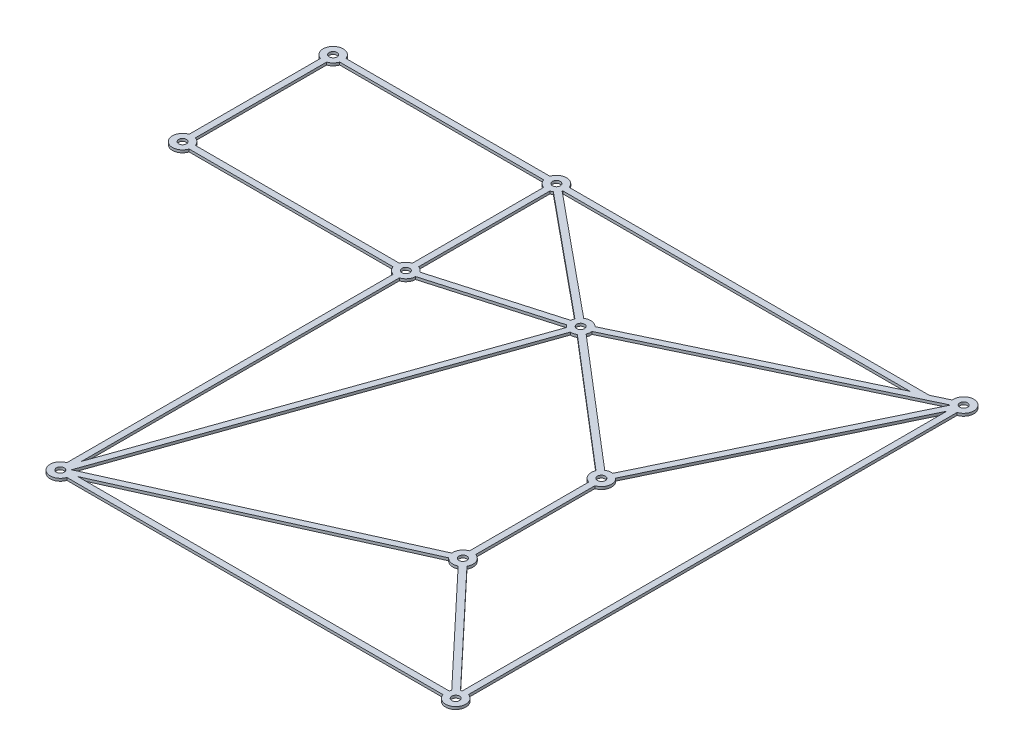
SolidWorks part; units mm, degrees
ref_plane "Front Plane" through (0, 0, 0) normal (0, 0, 1) x (1, 0, 0)
ref_plane "Top Plane" through (0, 0, 0) normal (0, 1, 0) x (1, 0, 0)
ref_plane "Right Plane" through (0, 0, 0) normal (1, 0, 0) x (0, 0, -1)
sketch "Sketch1" plane through (0, 0, 0) normal (0, 1, 0) x (1, 0, 0)
  line L0 (106.9742, -89.6492) -> (106.9742, -142.975) construction
  line L7 (0, -191.1) -> (152.3, -191.1) construction
  line L8 (152.3, -191.1) -> (152.3, 4.565) construction
  line L9 (106.9742, -89.6492) -> (106.9742, -142.975) construction
  line L10 (0, -191.1) -> (106.9742, -142.975) construction
  line L11 (106.9742, -142.975) -> (152.3, -191.1) construction
  line L12 (52.3, -42.975) -> (106.9742, -89.6492) construction
  line L13 (106.9742, -89.6492) -> (152.3, 4.565) construction
  line L14 (152.3, 4.565) -> (52.3, -42.975) construction
  line L15 (52.3, -42.975) -> (0, -191.1) construction
  line L16 (0, -192.3) -> (152.3, -192.3)
  line L17 (0.4923, -192.1944) -> (107.4665, -144.0694)
  line L18 (106.1006, -143.7977) -> (151.4264, -191.9227)
  line L19 (105.7742, -89.6492) -> (105.7742, -142.975)
  line L20 (153.5, -191.1) -> (153.5, 4.565)
  line L21 (108.0556, -90.1694) -> (153.3814, 4.0448)
  line L22 (151.7848, 5.6488) -> (51.7848, -41.8912)
  line L23 (51.5209, -43.8877) -> (106.1951, -90.5619)
  line L24 (51.1685, -42.5755) -> (-1.1315, -190.7005)
  line L25 (0, -189.9) -> (152.3, -189.9)
  line L26 (-0.4923, -190.0056) -> (106.4819, -141.8806)
  line L27 (107.8478, -142.1523) -> (153.1736, -190.2773)
  line L28 (108.1742, -89.6492) -> (108.1742, -142.975)
  line L29 (151.1, -191.1) -> (151.1, 4.565)
  line L30 (105.8928, -89.129) -> (151.2186, 5.0852)
  line L31 (152.8152, 3.4812) -> (52.8152, -44.0588)
  line L32 (53.0791, -42.0623) -> (107.7533, -88.7365)
  line L33 (53.4315, -43.3745) -> (1.1315, -191.4995)
  circle A1 centre (0, 0) radius 3.9 construction
  circle A2 centre (52.3, -42.975) radius 1.5
  circle A3 centre (152.3, 4.565) radius 1.5
  circle A4 centre (152.3, -191.1) radius 1.5
  circle A5 centre (0, -191.1) radius 1.5
  circle A6 centre (106.9742, -89.6492) radius 1.5
  circle A7 centre (106.9742, -142.975) radius 1.5
  circle A8 centre (106.9742, -89.6492) radius 3.9
  circle A9 centre (106.9742, -142.975) radius 3.9
  circle A10 centre (152.3, -191.1) radius 3.9
  circle A11 centre (0, -191.1) radius 3.9
  circle A12 centre (52.3, -42.975) radius 3.9
  circle A13 centre (152.3, 4.565) radius 3.9
  dimension "D11" = 3
  dimension "D2" = 4.565
  dimension "D3" = 195.665
  dimension "D4" = 152.3
  dimension "D5" = 52.3
  dimension "D6" = 42.975
  dimension "D7" = 53.3258
  dimension "D8" = 46.6742
  dimension "D9" = 54.6742
  dimension "D10" = 152.3
  dimension "D12" = 2.4
  dimension "D13" = 1.2
  dimension "D14" = 1.2
extrude "Boss-Extrude1" add sketch "Sketch1" along normal blind 20
sketch "Sketch2" plane through (0, 20, 0) normal (0, 1, 0) x (1, 0, 0)
  line L0 (153.5, -187.3892) -> (153.5, 0.8542) construction
  line L1 (151.1, -187.3892) -> (151.1, -0.6973) construction
  line L2 (105.7742, -93.36) -> (105.7742, -139.2642) construction
  line L3 (108.1742, -93.36) -> (108.1742, -139.2642) construction
  line L4 (153.5, -187.3892) -> (153.5, 0.8542)
  line L5 (151.1, -187.3892) -> (151.1, 0.8542)
  line L6 (105.7742, -93.36) -> (105.7742, -139.2642)
  line L7 (108.1742, -93.36) -> (108.1742, -139.2642)
  arc A0 (153.5, 0.8542) -> (148.4334, 4.0555) centre (152.3, 4.565) ccw construction
  arc A1 (55.1361, -40.298) -> (49.933, -46.0746) centre (52.3, -42.975) ccw construction
  arc A2 (108.1742, -93.36) -> (109.6643, -86.8255) centre (106.9742, -89.6492) ccw construction
  arc A3 (110.3919, -144.8536) -> (108.1742, -139.2642) centre (106.9742, -142.975) ccw construction
  arc A4 (148.5892, -192.3) -> (153.5, -187.3892) centre (152.3, -191.1) ccw construction
  arc A5 (0.1039, -187.2014) -> (3.7108, -192.3) centre (0, -191.1) ccw construction
  arc A6 (153.5, 0.8542) -> (148.4334, 4.0555) centre (152.3, 4.565) ccw
  arc A7 (55.1361, -40.298) -> (49.933, -46.0746) centre (52.3, -42.975) ccw
  arc A8 (108.1742, -93.36) -> (109.6643, -86.8255) centre (106.9742, -89.6492) ccw
  arc A9 (110.3919, -144.8536) -> (108.1742, -139.2642) centre (106.9742, -142.975) ccw
  arc A10 (148.5892, -192.3) -> (153.5, -187.3892) centre (152.3, -191.1) ccw
  arc A11 (0.1039, -187.2014) -> (3.7108, -192.3) centre (0, -191.1) ccw
  circle A12 centre (52.3, -42.975) radius 3.9
  circle A13 centre (152.3, 4.565) radius 3.9
  circle A14 centre (106.9742, -89.6492) radius 3.9
  circle A15 centre (0, -191.1) radius 3.9
  circle A16 centre (106.9742, -142.975) radius 3.9
  circle A17 centre (152.3, -191.1) radius 3.9
  circle M1 centre (106.9742, -142.975) radius 1.5
  circle M2 centre (152.3, -191.1) radius 1.5
  arc M5 (104.0824, -145.5918) -> (108.6448, -146.4991) centre (106.9742, -142.975) ccw
  arc M7 (148.8823, -189.2214) -> (148.5892, -189.9) centre (152.3, -191.1) ccw
  circle M8 centre (106.9742, -89.6492) radius 1.5
  line M10 (151.1, -0.6973) -> (151.1, -187.3892)
  arc M11 (151.1, -187.3892) -> (150.6294, -187.5759) centre (152.3, -191.1) ccw
  arc M13 (110.3919, -144.8536) -> (108.1742, -139.2642) centre (106.9742, -142.975) ccw
  line M14 (108.1742, -139.2642) -> (108.1742, -93.36)
  arc M15 (108.1742, -93.36) -> (109.6643, -86.8255) centre (106.9742, -89.6492) ccw
  circle M16 centre (152.3, 4.565) radius 1.5
  arc M17 (55.9014, -44.4716) -> (56.1666, -42.4655) centre (52.3, -42.975) ccw
  arc M19 (149.4639, 1.888) -> (149.6099, 1.7413) centre (152.3, 4.565) ccw
  arc M21 (107.5016, -85.785) -> (104.9311, -86.3272) centre (106.9742, -89.6492) ccw
  line M23 (2.0652, -188.8551) -> (52.1961, -46.8736)
  arc M24 (52.1961, -46.8736) -> (54.3431, -46.297) centre (52.3, -42.975) ccw
  arc M26 (103.3728, -88.1526) -> (105.7742, -93.36) centre (106.9742, -89.6492) ccw
  line M27 (105.7742, -93.36) -> (105.7742, -139.2642)
  arc M28 (105.7742, -139.2642) -> (103.0978, -143.4031) centre (106.9742, -142.975) ccw
  line M29 (103.0978, -143.4031) -> (2.0652, -188.8551)
  arc M31 (55.1361, -40.298) -> (49.933, -46.0746) centre (52.3, -42.975) ccw
  arc M33 (0.1039, -187.2014) -> (3.7108, -192.3) centre (0, -191.1) ccw
  arc M35 (148.5892, -192.3) -> (153.5, -187.3892) centre (152.3, -191.1) ccw
  line M36 (153.5, -187.3892) -> (153.5, 0.8542)
  arc M37 (153.5, 0.8542) -> (148.4334, 4.0555) centre (152.3, 4.565) ccw
  circle M38 centre (52.3, -42.975) radius 1.5
  circle M39 centre (0, -191.1) radius 1.5
extrude "Boss-Extrude2" add sketch "Sketch2" along normal blind 4.8 contours A17 A13 L5 M36 M10 | A13 M37 M19 M16 | A17 M35 M11 M7 M2 | A16 A14 M14 M27 | A16 M5 M13 M28 M1 | A14 M15 M21 M26 M8 | A15 M33 M29 M23 M39 | A12 M24 M17 M31 M38
sketch "Sketch3" plane through (0, 0, 0) normal (0, -1, 0) x (1, 0, 0)
  line L0 (0, 58) -> (0, 0) construction
  line L1 (0, 191.1) -> (0, 58) construction
  line L2 (0, 58) -> (52.3, 42.975) construction
  line L3 (52.3, 42.975) -> (0, 0) construction
  line L4 (0, 0) -> (152.3, 0) construction
  line L5 (-1.2, 191.1) -> (-1.2, 58)
  line L6 (-1.2, 58) -> (-1.2, 0)
  line L7 (-0.3313, 56.8467) -> (49.7736, 42.4522)
  line L8 (49.7736, 42.4522) -> (-0.7618, 0.9271)
  line L9 (0, -1.2) -> (152.3, -1.2)
  line L10 (1.2, 191.1) -> (1.2, 58)
  line L11 (1.2, 58) -> (1.2, 0)
  line L12 (0.3313, 59.1533) -> (54.8264, 43.4978)
  line L13 (54.8264, 43.4978) -> (0.7618, -0.9271)
  line L14 (0, 1.2) -> (152.3, 1.2)
  line L15 (-86, 0) -> (0, 0) construction
  line L16 (-86, 0) -> (-86, 58) construction
  line L17 (-86, 58) -> (0, 58) construction
  line L18 (-84.8, 1.2) -> (0, 1.2)
  line L19 (-84.8, 1.2) -> (-84.8, 56.8)
  line L20 (-84.8, 56.8) -> (0, 56.8)
  line L21 (-87.2, -1.2) -> (0, -1.2)
  line L22 (-87.2, -1.2) -> (-87.2, 59.2)
  line L23 (-87.2, 59.2) -> (0, 59.2)
  circle A0 centre (0, 0) radius 1.5
  circle A1 centre (0, 58) radius 1.5
  circle A2 centre (0, 58) radius 3.9
  circle A3 centre (0, 0) radius 3.9
  circle A4 centre (0, 191.1) radius 1.5 construction
  circle A6 centre (52.3, 42.975) radius 1.5 construction
  circle A7 centre (0, 191.1) radius 1.5
  circle A9 centre (52.3, 42.975) radius 1.5
  arc A11 (54.3431, 46.297) -> (52.1961, 46.8736) centre (52.3, 42.975) ccw construction
  circle A12 centre (-86, 58) radius 3.9
  circle A13 centre (-86, 0) radius 3.9
  circle A14 centre (-86, 58) radius 1.5
  circle A15 centre (-86, 0) radius 1.5
  line M11 (55.1361, 40.298) -> (148.4334, -4.0555)
  arc M12 (148.4334, -4.0555) -> (153.5, -0.8542) centre (152.3, -4.565) ccw
  arc M16 (3.7108, 192.3) -> (0.1039, 187.2014) centre (0, 191.1) ccw
  line M17 (0.1039, 187.2014) -> (49.933, 46.0746)
  arc M18 (49.933, 46.0746) -> (55.1361, 40.298) centre (52.3, 42.975) ccw
  dimension "D3" = 58
  dimension "D4" = 86
  dimension "D1" = 1.2
  dimension "D2" = 1.2
  dimension "D5" = 1.2
  dimension "D6" = 1.2
extrude "Boss-Extrude3" add sketch "Sketch3" against normal blind 5 separate body contours A2 L10 L5 M17 M16 | A2 L7 L12 M18 | L7 A2 L12 L10 A1 L11 | L12 A2 L10 | L10 A2 L5 A1 L12 | L5 A2 L6 A1 | L6 A2 L11 L7 A1 | L11 A2 L7 | A3 L11 A2 L6 | A3 L13 L8 M18 | L13 A3 L8 L11 L14 | L8 A3 L11 | A0 L14 L11 L8 | L11 A3 L6 A0 L8 | A0 L13 L14 L11 | A0 L11 L14 | L9 A3 L14 L13 A0 | A3 L9 L14 M12 M11 | L14 A3 L13 | L5 A2 L23 | A12 L20 A2 L23 | L6 A3 L18 | L18 A3 L21 A0 L6 | L21 A3 L9 A0 | A13 L21 A3 L18 | A15 L21 A13 L18 L19 L22 | L18 A13 L19 | A15 L22 A13 L21 | A13 L19 A12 L22 | L19 A12 L20 | A14 L22 A12 L19 L20 L23 | A14 L23 A12 L22 | A14 L23 L22 | A15 L22 L21 | L20 A2 L6 | A1 L10 L12 | A1 L7 L11 | A1 L6 L20 | A1 L23 L5 | A0 L18 L6
sketch "Sketch4" plane through (0, 5, 0) normal (0, 1, 0) x (1, 0, 0)
  circle A0 centre (0, -58) radius 1.5
  circle A1 centre (0, 0) radius 1.5 construction
extrude "Cut-Extrude1" cut sketch "Sketch4" against normal through all
sketch "Sketch5" plane through (0, 5, 0) normal (0, 1, 0) x (1, 0, 0)
  circle A0 centre (-86, 0) radius 1.5 construction
  circle A1 centre (-86, -58) radius 1.5 construction
  circle A2 centre (0, -58) radius 1.5 construction
  circle A3 centre (0, 0) radius 1.5 construction
  circle A4 centre (-86, 0) radius 1.5
  circle A5 centre (-86, -58) radius 1.5
  circle A6 centre (0, -58) radius 1.5
  circle A7 centre (0, 0) radius 1.5
  arc A8 (-3.7108, -1.2) -> (-1.2, -3.7108) centre (0, 0) ccw construction
  arc A9 (-3.7108, -59.2) -> (-1.2, -61.7108) centre (0, -58) ccw construction
  arc A10 (-87.2, -54.2892) -> (-82.2892, -59.2) centre (-86, -58) ccw construction
  arc A11 (-82.2892, 1.2) -> (-87.2, -3.7108) centre (-86, 0) ccw construction
  arc A12 (-3.7108, -1.2) -> (-1.2, -3.7108) centre (0, 0) ccw
  arc A13 (-3.7108, -59.2) -> (-1.2, -61.7108) centre (0, -58) ccw
  arc A14 (-87.2, -54.2892) -> (-82.2892, -59.2) centre (-86, -58) ccw
  arc A15 (-82.2892, 1.2) -> (-87.2, -3.7108) centre (-86, 0) ccw
  circle A16 centre (-86, 0) radius 3.9
  circle A17 centre (-86, -58) radius 3.9
  circle A18 centre (0, -58) radius 3.9
  circle A19 centre (0, 0) radius 3.9
  circle M1 centre (0, -58) radius 1.5
  arc M2 (3.2352, -55.822) -> (1.2, -54.2892) centre (0, -58) ccw
  arc M4 (1.2, -3.7108) -> (2.1052, -3.283) centre (0, 0) ccw
  arc M8 (3.6289, -1.4287) -> (3.7108, -1.2) centre (0, 0) ccw
  arc M13 (3.7108, 1.2) -> (-3.7108, 1.2) centre (0, 0) ccw
  arc M15 (-82.2892, 1.2) -> (-87.2, -3.7108) centre (-86, 0) ccw
  arc M17 (-87.2, -54.2892) -> (-82.2892, -59.2) centre (-86, -58) ccw
  arc M19 (-3.7108, -59.2) -> (-1.2, -61.7108) centre (0, -58) ccw
  arc M24 (1.2, -61.7108) -> (3.8979, -58.1287) centre (0, -58) ccw
  circle M28 centre (0, 0) radius 1.5
  circle M29 centre (-86, 0) radius 1.5
  arc M31 (-1.2, -54.2892) -> (-3.7108, -56.8) centre (0, -58) ccw
  arc M33 (-82.2892, -56.8) -> (-84.8, -54.2892) centre (-86, -58) ccw
  arc M35 (-84.8, -3.7108) -> (-82.2892, -1.2) centre (-86, 0) ccw
  arc M37 (-3.7108, -1.2) -> (-1.2, -3.7108) centre (0, 0) ccw
  circle M38 centre (-86, -58) radius 1.5
extrude "Boss-Extrude4" add sketch "Sketch5" along normal blind 4.7 contours A16 M35 M15 M29 | A17 M17 M33 M38 | A18 M24 M2 M31 M19 M1 | A19 M4 M8 M13 M37 M28
sketch "Sketch6" plane through (0, 0, 0) normal (0, -1, 0) x (1, 0, 0)
  line L8 (3.7108, -1.2) -> (142.4268, -1.2)
  line L9 (142.4268, -1.2) -> (148.4334, -4.0555)
  line L10 (153.5, -0.8542) -> (153.5, 187.3892)
  line L11 (148.5892, 192.3) -> (3.7108, 192.3)
  line L12 (-1.2, 187.3892) -> (-1.2, 61.7108)
  line L13 (-3.7108, 59.2) -> (-82.2892, 59.2)
  line L14 (-87.2, 54.2892) -> (-87.2, 3.7108)
  line L15 (-82.2892, -1.2) -> (-3.7108, -1.2)
  line L16 (3.7108, -1.2) -> (142.4268, -1.2)
  line L17 (142.4268, -1.2) -> (148.4334, -4.0555)
  line L18 (153.5, -0.8542) -> (153.5, 187.3892)
  line L19 (148.5892, 192.3) -> (3.7108, 192.3)
  line L20 (-1.2, 187.3892) -> (-1.2, 61.7108)
  line L21 (-3.7108, 59.2) -> (-82.2892, 59.2)
  line L22 (-87.2, 54.2892) -> (-87.2, 3.7108)
  line L23 (-82.2892, -1.2) -> (-3.7108, -1.2)
  arc A7 (148.4334, -4.0555) -> (153.5, -0.8542) centre (152.3, -4.565) ccw
  arc A8 (153.5, 187.3892) -> (148.5892, 192.3) centre (152.3, 191.1) ccw
  arc A9 (3.7108, 192.3) -> (-1.2, 187.3892) centre (0, 191.1) ccw
  arc A10 (-1.2, 61.7108) -> (-3.7108, 59.2) centre (0, 58) ccw
  arc A11 (-82.2892, 59.2) -> (-87.2, 54.2892) centre (-86, 58) ccw
  arc A12 (-87.2, 3.7108) -> (-82.2892, -1.2) centre (-86, 0) ccw
  arc A13 (-3.7108, -1.2) -> (3.7108, -1.2) centre (0, 0) ccw
  arc A14 (148.4334, -4.0555) -> (153.5, -0.8542) centre (152.3, -4.565) ccw
  arc A15 (153.5, 187.3892) -> (148.5892, 192.3) centre (152.3, 191.1) ccw
  arc A16 (3.7108, 192.3) -> (-1.2, 187.3892) centre (0, 191.1) ccw
  arc A17 (-1.2, 61.7108) -> (-3.7108, 59.2) centre (0, 58) ccw
  arc A18 (-82.2892, 59.2) -> (-87.2, 54.2892) centre (-86, 58) ccw
  arc A19 (-87.2, 3.7108) -> (-82.2892, -1.2) centre (-86, 0) ccw
  arc A20 (-3.7108, -1.2) -> (3.7108, -1.2) centre (0, 0) ccw
  dimension "D1" = 0
extrude "Cut-Extrude2" cut sketch "Sketch6" along direction (0, 1, 0) on the side against the normal through all from offset 1 contours L16 L17 A14 L18 A15 L19 A16 L20 A17 L21 A18 L22 A19 L23 A20
